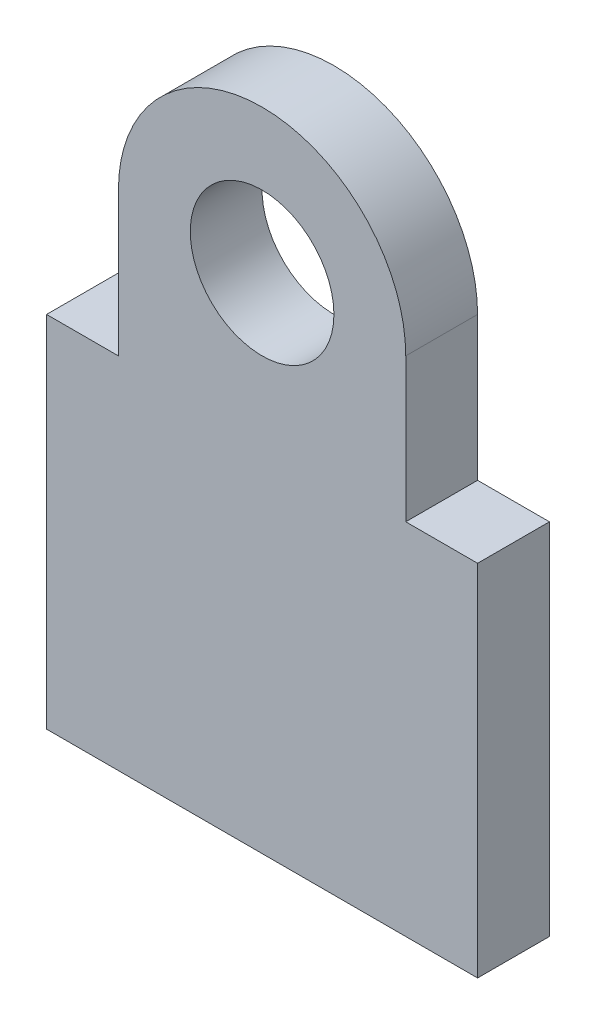
SolidWorks part; units mm, degrees
ref_plane "Front Plane" through (0, 0, 0) normal (0, 0, 1) x (1, 0, 0)
ref_plane "Top Plane" through (0, 0, 0) normal (0, 1, 0) x (1, 0, 0)
ref_plane "Right Plane" through (0, 0, 0) normal (1, 0, 0) x (0, 0, -1)
sketch "Sketch1" plane through (0, 0, 0) normal (0, 0, 1) x (1, 0, 0)
  line L0 (-30, 0) -> (30, 0)
  line L1 (30, 0) -> (30, 20)
  line L2 (30, 20) -> (20, 20)
  line L3 (20, 20) -> (20, 40)
  line L6 (0, 40) -> (0, 0) construction
  line L7 (-20, 20) -> (-20, 40)
  line L8 (-30, 20) -> (-20, 20)
  line L9 (-30, 0) -> (-30, 20)
  arc A0 (20, 40) -> (-20, 40) centre (0, 40) ccw
  dimension "D5" = 20
  dimension "D2" = 20
  dimension "D3" = 10
  dimension "D4" = 20
extrude "Boss-Extrude1" add sketch "Sketch1" along normal blind 10
sketch "Sketch2" plane through (0, 0, 10) normal (0, 0, 1) x (1, 0, 0)
  circle A0 centre (0, 40) radius 10
  dimension "D1" = 20
extrude "Boss-Extrude2" add sketch "Sketch2" along normal blind 20
sketch "Sketch3" plane through (0, 0, 10) normal (0, 0, 1) x (1, 0, 0)
  line L0 (-30, 0) -> (-30, -30)
  line L1 (-30, -30) -> (30, -30)
  line L2 (30, -30) -> (30, 0)
  line L3 (30, 0) -> (-30, 0)
extrude "Boss-Extrude3" add sketch "Sketch3" against normal blind 10
sketch "Sketch4" plane through (0, 0, 30) normal (0, 0, 1) x (1, 0, 0)
  circle A0 centre (0, 40) radius 10
extrude "Cut-Extrude1" cut sketch "Sketch4" against normal blind 30
